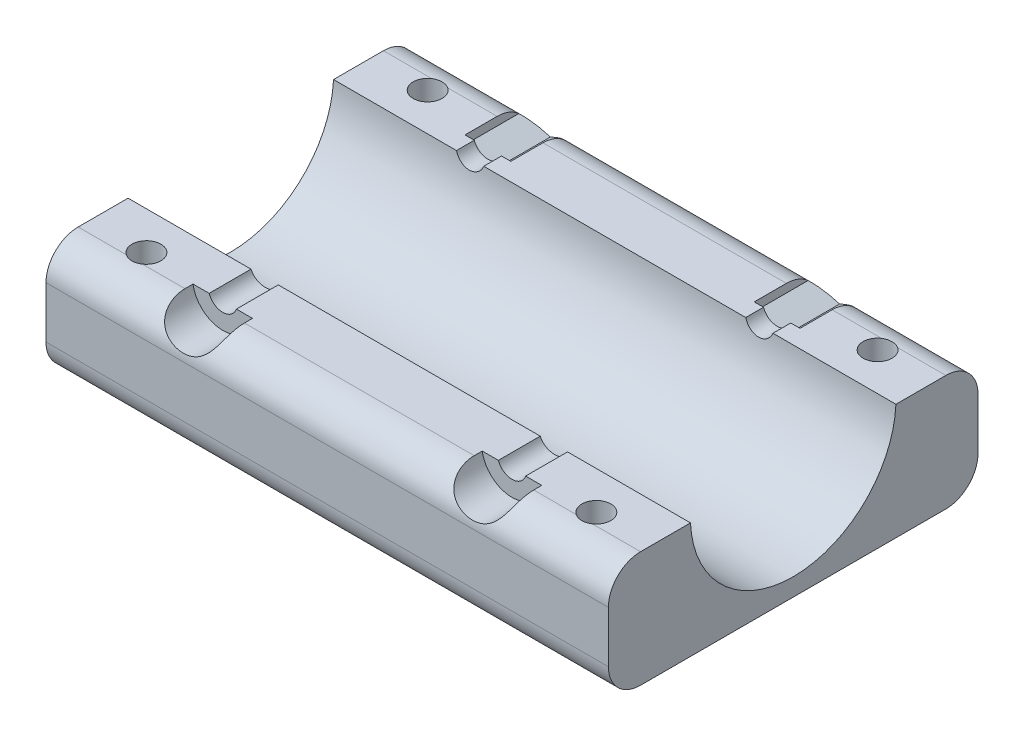
SolidWorks part; units mm, degrees
ref_plane "Front Plane" through (0, 0, 0) normal (0, 0, 1) x (1, 0, 0)
ref_plane "Top Plane" through (0, 0, 0) normal (0, 1, 0) x (1, 0, 0)
ref_plane "Right Plane" through (0, 0, 0) normal (1, 0, 0) x (0, 0, -1)
sketch "Sketch1" plane through (0, 0, 0) normal (1, 0, 0) x (0, 0, -1)
  line L0 (-19, -15) -> (19, -15)
  line L1 (23, -11) -> (23, -4.6)
  line L2 (19, -0.6) -> (-19, -0.6)
  line L3 (-23, -4.6) -> (-23, -11)
  arc A0 (19, -15) -> (23, -11) centre (19, -11) ccw
  arc A1 (23, -4.6) -> (19, -0.6) centre (19, -4.6) ccw
  arc A2 (-19, -0.6) -> (-23, -4.6) centre (-19, -4.6) ccw
  arc A3 (-23, -11) -> (-19, -15) centre (-19, -11) ccw
extrude "Boss-Extrude1" add sketch "Sketch1" along normal mid plane 70
sketch "Sketch2" plane through (0, 0, 0) normal (1, 0, 0) x (0, 0, -1)
  circle A0 centre (0, 0) radius 12.8
extrude "Cut-Extrude1" cut sketch "Sketch2" against normal through all and the other way through all
ref_plane "Plane1" through (0, -15, 0) normal (0, 1, 0) x (1, 0, 0)
sketch "Sketch3" plane through (0, -15, 0) normal (0, 1, 0) x (1, 0, 0)
  circle A0 centre (28, -17.5) radius 1.8
  circle A1 centre (28, 17.5) radius 1.8
  circle A2 centre (-28, -17.5) radius 1.8
  circle A3 centre (-28, 17.5) radius 1.8
extrude "Cut-Extrude2" cut sketch "Sketch3" along normal blind 16
ref_plane "Plane2" through (0, -15, 0) normal (0, 1, 0) x (1, 0, 0)
sketch "Sketch4" plane through (0, -15, 0) normal (0, 1, 0) x (1, 0, 0)
  circle A0 centre (28, -17.5) radius 3.25
  circle A1 centre (28, 17.5) radius 3.25
  circle A2 centre (-28, -17.5) radius 3.25
  circle A3 centre (-28, 17.5) radius 3.25
extrude "Cut-Extrude3" cut sketch "Sketch4" along normal blind 5.6
sketch "Sketch5" plane through (0, 0, 0) normal (0, 0, 1) x (1, 0, 0)
  circle A0 centre (18, 0) radius 1.8
  circle A1 centre (-18, 0) radius 1.8
extrude "Cut-Extrude4" cut sketch "Sketch5" against normal through all and the other way through all
ref_plane "Plane3" through (0, 0, 23) normal (0, 0, 1) x (1, 0, 0)
sketch "Sketch6" plane through (0, 0, 23) normal (0, 0, 1) x (1, 0, 0)
  circle A0 centre (18, 0) radius 3.75
  circle A1 centre (-18, 0) radius 3.75
extrude "Cut-Extrude5" cut sketch "Sketch6" against normal blind 5
ref_plane "Plane4" through (0, 0, -23) normal (0, 0, 1) x (1, 0, 0)
sketch "Sketch7" plane through (0, 0, -23) normal (0, 0, 1) x (1, 0, 0)
  line L0 (20.85, 1.6454) -> (18, 3.2909)
  line L1 (18, 3.2909) -> (15.15, 1.6454)
  line L2 (15.15, 1.6454) -> (15.15, -1.6454)
  line L3 (15.15, -1.6454) -> (18, -3.2909)
  line L4 (18, -3.2909) -> (20.85, -1.6454)
  line L5 (20.85, -1.6454) -> (20.85, 1.6454)
  line L6 (-15.15, 1.6454) -> (-18, 3.2909)
  line L7 (-18, 3.2909) -> (-20.85, 1.6454)
  line L8 (-20.85, 1.6454) -> (-20.85, -1.6454)
  line L9 (-20.85, -1.6454) -> (-18, -3.2909)
  line L10 (-18, -3.2909) -> (-15.15, -1.6454)
  line L11 (-15.15, -1.6454) -> (-15.15, 1.6454)
extrude "Cut-Extrude6" cut sketch "Sketch7" along normal blind 8
